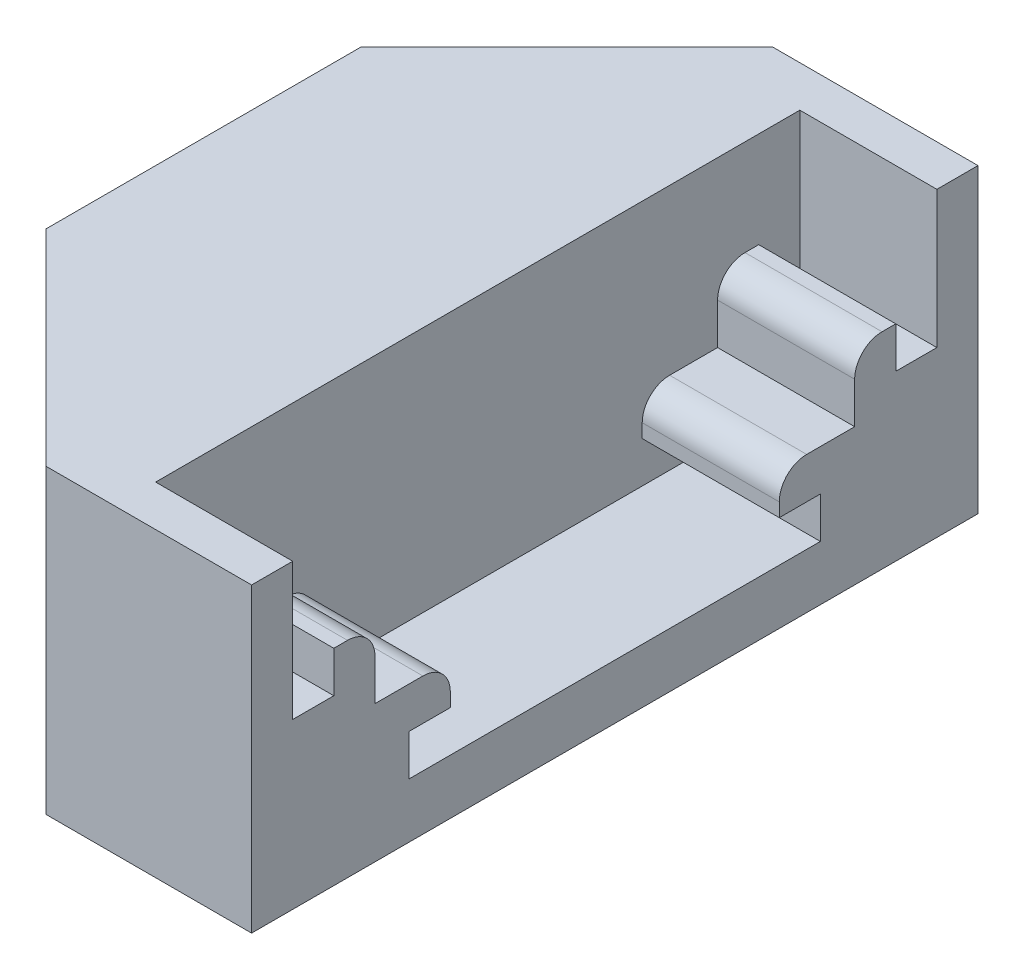
SolidWorks part; units mm, degrees
material "ABS"
ref_plane "Front Plane" through (0, 0, 0) normal (0, 0, 1) x (1, 0, 0)
ref_plane "Top Plane" through (0, 0, 0) normal (0, 1, 0) x (1, 0, 0)
ref_plane "Right Plane" through (0, 0, 0) normal (1, 0, 0) x (0, 0, -1)
sketch "Sketch1" plane through (0, 0, 0) normal (1, 0, 0) x (0, 0, -1)
  line L1 (-26.5, -27.5) -> (-26.5, -5.5)
  line L7 (-23.5, -5.5) -> (-23.5, -15.5)
  line L8 (-23.5, -15.5) -> (-20.5, -15.5)
  line L9 (-20.5, -15.5) -> (-20.5, -12.5)
  line L10 (-20.5, -12.5) -> (-17.5, -12.5)
  line L11 (-17.5, -12.5) -> (-17.5, -17.5)
  line L12 (-17.5, -17.5) -> (-12, -17.5)
  line L14 (-12, -20.5) -> (-15, -20.5)
  line L15 (-15, -20.5) -> (-15, -23.5)
  line L18 (-12, -20.5) -> (-12, -17.5)
  line L19 (0, -27.5) -> (0, -23.5) construction
  line L35 (-23.5, -5.5) -> (-26.5, -5.5)
  line L37 (0, -23.5) -> (0, -27.5) construction
  line L50 (-15, -23.5) -> (0, -23.5)
  line L51 (0, -23.5) -> (0, -27.5)
  line L52 (0, -27.5) -> (-26.5, -27.5)
  dimension "D1" = 3
  dimension "D2" = 3
  dimension "D3" = 3
  dimension "D4" = 20.5
  dimension "D5" = 15
  dimension "D6" = 3
  dimension "D7" = 20.5
  dimension "D8" = 0
  dimension "D9" = 3
  dimension "3" = 3
  dimension "D11" = 10
  dimension "D12" = 3
extrude "Boss-Extrude1" add sketch "Sketch1" along normal blind 10
fillet "Fillet1" radius 2 2 edges at (5, -17.5, 12) (5, -12.5, 17.5)
sketch "Sketch2" plane through (0, 0, 0) normal (-1, 0, 0) x (0, 0, 1)
  line L0 (0, -27.5) -> (0, -23.5) construction
  line L5 (26.5, -5.5) -> (0, -5.5)
  line L6 (26.5, -5.5) -> (26.5, -27.5)
  line L7 (26.5, -27.5) -> (0, -27.5)
  line L8 (0, -5.5) -> (0, -27.5)
extrude "Boss-Extrude2" add sketch "Sketch2" along normal blind 20
chamfer "Chamfer1" distance 15 angle 45 1 edges at (-20, -16.5, 26.5)
mirror "Mirror1" about plane through (10, -23.5, 0) normal (0, 0, 1) of bodies 102 104
